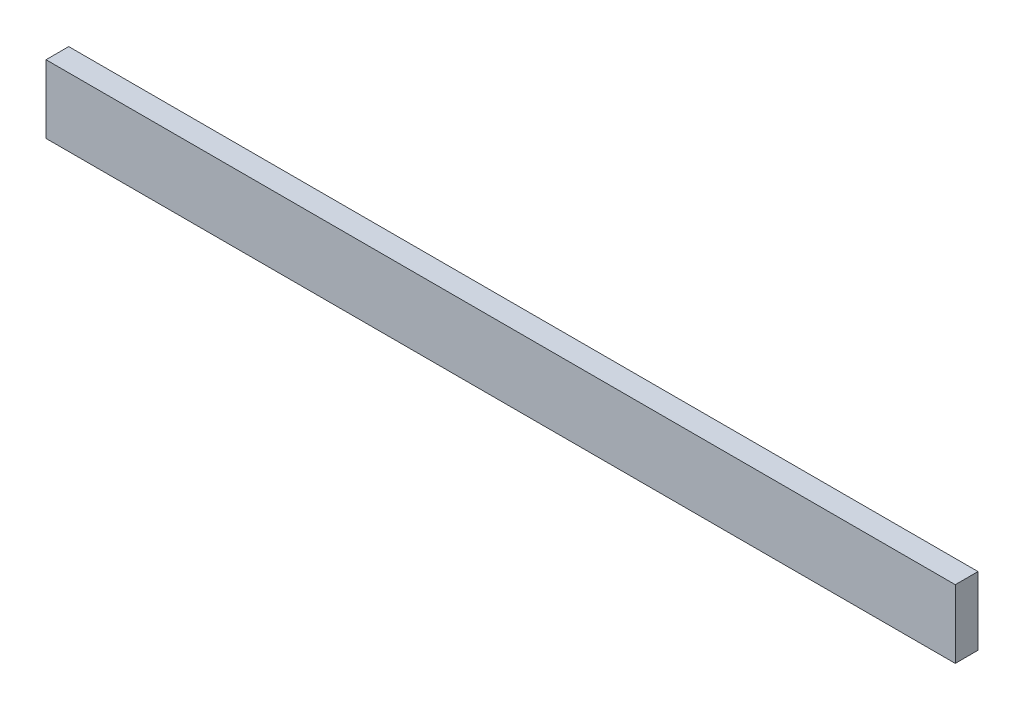
SolidWorks part; units mm, degrees
material "Plain Carbon Steel"
ref_plane "Front Plane" through (0, 0, 0) normal (0, 0, 1) x (1, 0, 0)
ref_plane "Top Plane" through (0, 0, 0) normal (0, 1, 0) x (1, 0, 0)
ref_plane "Right Plane" through (0, 0, 0) normal (1, 0, 0) x (0, 0, -1)
sketch "Sketch1" plane through (0, 0, 0) normal (1, 0, 0) x (0, 0, -1)
  line L1 (-12.7, -38.1) -> (12.7, -38.1)
  line L2 (-12.7, -38.1) -> (-12.7, 38.1)
  line L3 (-12.7, 38.1) -> (12.7, 38.1)
  line L4 (12.7, -38.1) -> (12.7, 38.1)
  line L5 (-12.7, -38.1) -> (12.7, 38.1) construction
  line L6 (-12.7, 38.1) -> (12.7, -38.1) construction
  point P0 (0, 0)
  dimension "D1" = 76.2
  dimension "D2" = 25.4
extrude "Boss-Extrude1" add sketch "Sketch1" along normal mid plane 1016
